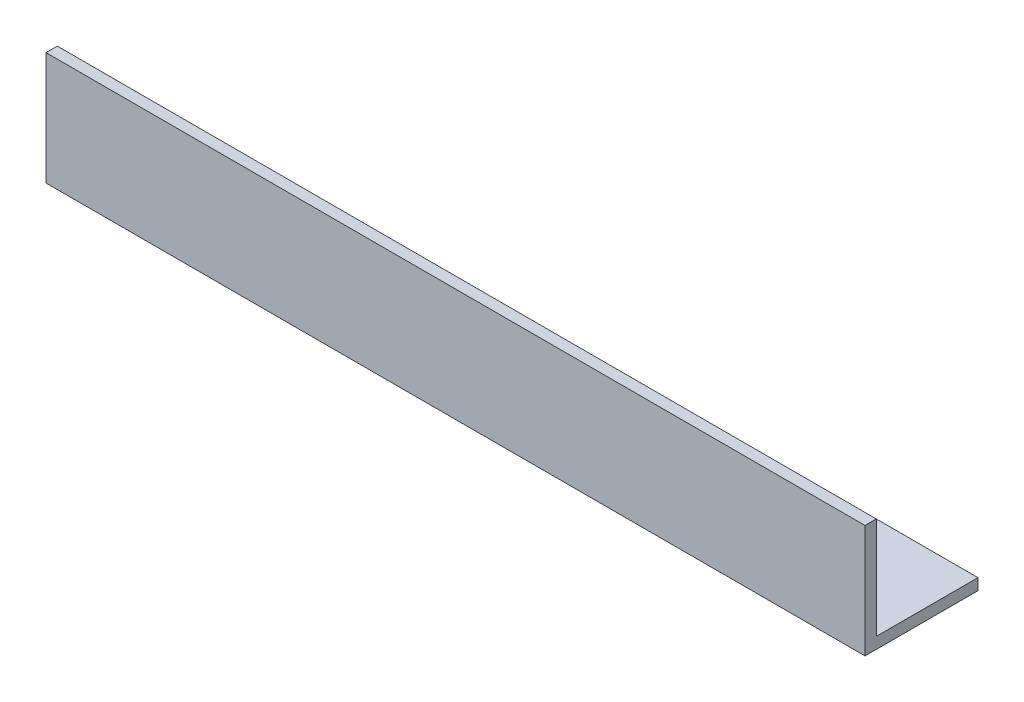
SolidWorks part; units mm, degrees
ref_plane "Front Plane" through (0, 0, 0) normal (0, 0, 1) x (1, 0, 0)
ref_plane "Top Plane" through (0, 0, 0) normal (0, 1, 0) x (1, 0, 0)
ref_plane "Right Plane" through (0, 0, 0) normal (1, 0, 0) x (0, 0, -1)
sketch "Sketch1" plane through (0, 0, 0) normal (1, 0, 0) x (0, 0, -1)
  line L0 (0, 20) -> (0, 0)
  line L1 (0, 0) -> (20, 0)
  line L2 (20, 0) -> (20, 2)
  line L3 (20, 2) -> (2, 2)
  line L4 (2, 2) -> (2, 20)
  line L5 (2, 20) -> (0, 20)
  dimension "D1" = 20
  dimension "D2" = 20
  dimension "D3" = 2
  dimension "D4" = 2
extrude "Boss-Extrude1" add sketch "Sketch1" along normal blind 145
sketch "Sketch2" plane through (0, 2, 0) normal (0, 1, 0) x (1, 0, 0)
  line L0 (145, 20) -> (0, 20) construction
  line L1 (0, 20) -> (0, 2) construction
  circle A0 centre (8, 11) radius 2.5
  circle A1 centre (40, 11) radius 2.5
  dimension "D3" = 5
  dimension "D4" = 5
  dimension "D1" = 9
  dimension "D2" = 8
  dimension "D5" = 40
extrude "Cut-Extrude1" cut sketch "Sketch2" against normal blind 2
